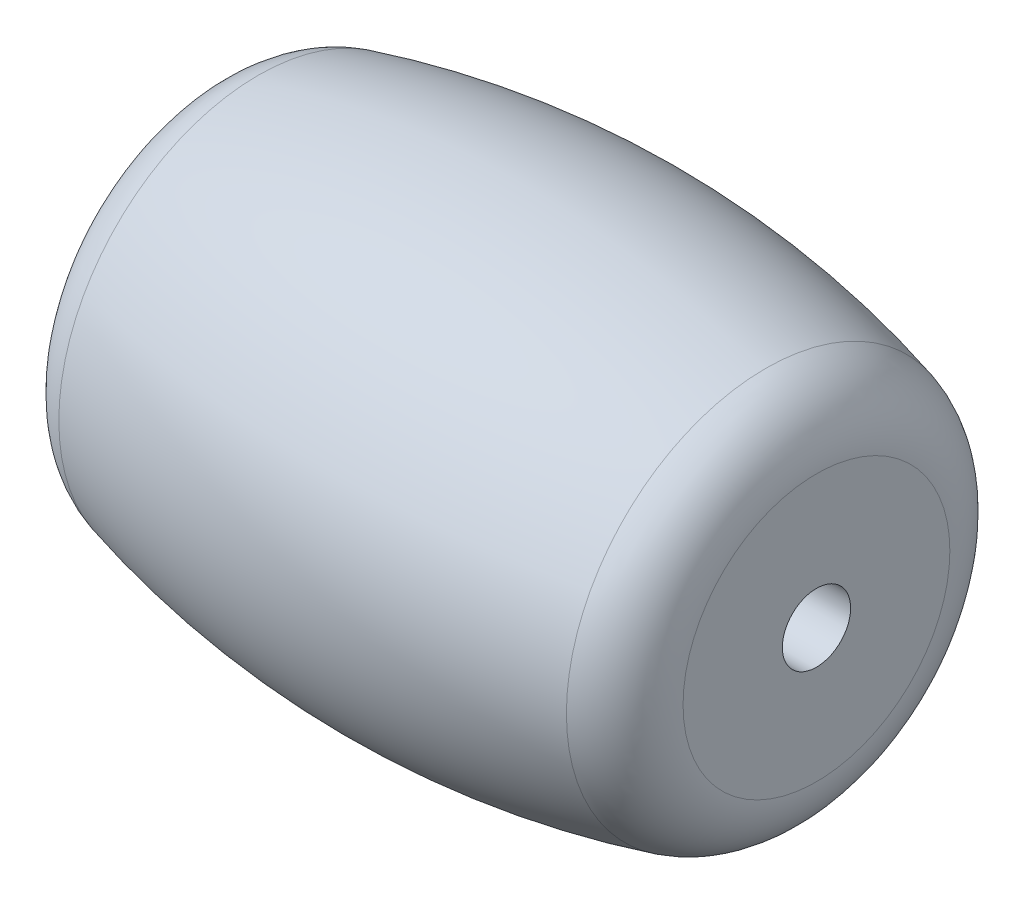
SolidWorks part; units mm, degrees
material "PTFE (général)"
ref_plane "Plan de face" through (0, 0, 0) normal (0, 0, 1) x (1, 0, 0)
ref_plane "Plan de dessus" through (0, 0, 0) normal (0, 1, 0) x (1, 0, 0)
ref_plane "Plan de droite" through (0, 0, 0) normal (1, 0, 0) x (0, 0, -1)
sketch "Esquisse1" plane through (0, 0, 0) normal (0, 0, 1) x (1, 0, 0)
  line L0 (0, 0) -> (-26.75, 0) construction
  line L1 (-13.375, 0) -> (-13.375, 8.1)
  line L2 (-26.4496, 10.22) -> (29.6728, 10.22) construction
  line L3 (13.375, 8.1) -> (13.375, 0)
  line L4 (-13.375, 0) -> (13.375, 0)
  arc A0 (13.375, 8.1) -> (-13.375, 8.1) centre (0, -33.0312) ccw
  dimension "D1" = 10.22
  dimension "D2" = 26.75
  dimension "D3" = 8.1
  dimension "D4" = 13.375
revolve "Révolution1" add sketch "Esquisse1" angle 360 about L0
fillet "Congé1" radius 3 2 edges at (-13.375, 0, -8.1) (13.375, 0, -8.1)
sketch "Esquisse2" plane through (13.375, 0, 0) normal (1, 0, 0) x (0, 0, -1)
  circle A0 centre (0, 0) radius 1.5
  dimension "D1" = 3
extrude "Enlèv. mat.-Extru.1" cut sketch "Esquisse2" against normal through all
